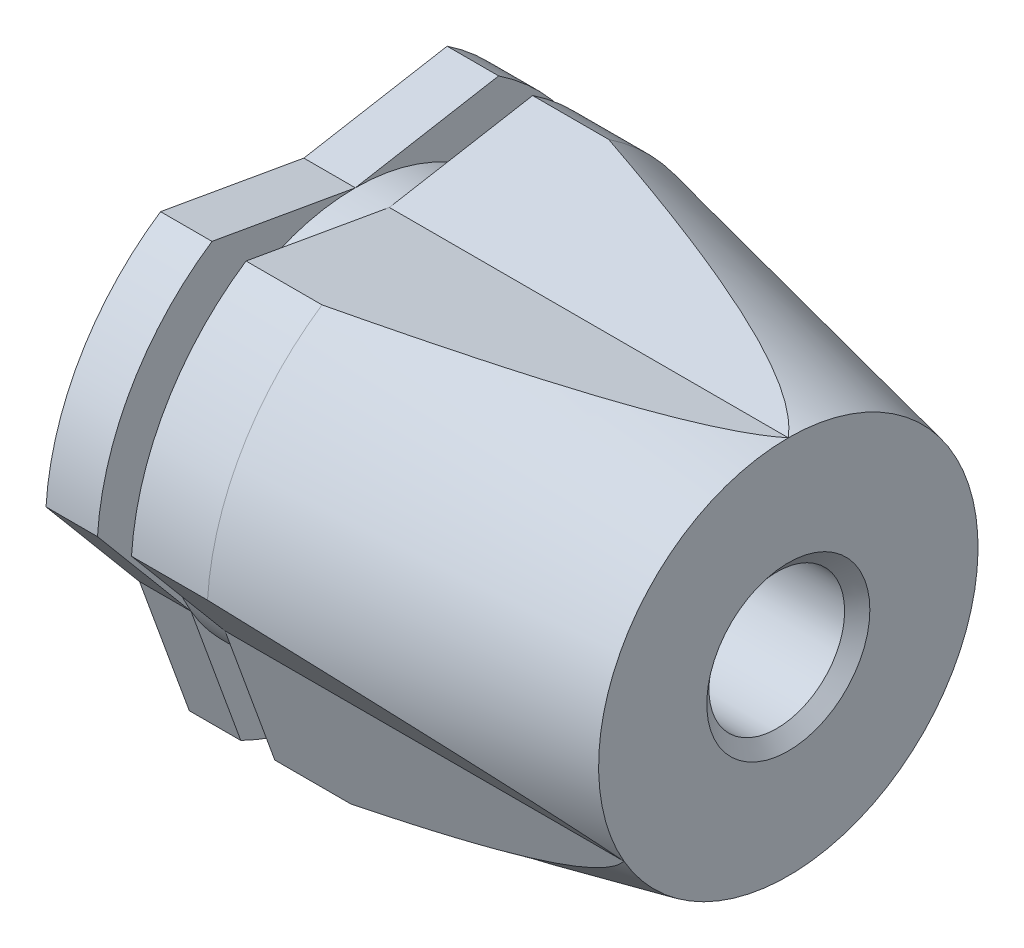
SolidWorks part; units mm, degrees
material "1023 Carbon Steel Sheet (SS)"
ref_plane "Front Plane" through (0, 0, 0) normal (0, 0, 1) x (1, 0, 0)
ref_plane "Top Plane" through (0, 0, 0) normal (0, 1, 0) x (1, 0, 0)
ref_plane "Right Plane" through (0, 0, 0) normal (1, 0, 0) x (0, 0, -1)
sketch "Sketch1" plane through (0, 0, 0) normal (1, 0, 0) x (0, 0, -1)
  circle A0 centre (0, 0) radius 8
  dimension "D1" = 16
extrude "Boss-Extrude1" add sketch "Sketch1" along normal blind 5
sketch "Sketch2" plane through (5, 0, 0) normal (1, 0, 0) x (0, 0, -1)
  circle A0 centre (0, 0) radius 8 construction
  circle A1 centre (0, 0) radius 8
extrude "Boss-Extrude2" add sketch "Sketch2" along normal blind 10 draft 12
sketch "Sketch3" plane through (15, 0, 0) normal (1, 0, 0) x (0, 0, -1)
  line L0 (0, 0) -> (0, 11.4181) construction
  line L1 (0, 5.8744) -> (11.4069, 7.8858)
  line L2 (0, 5.8744) -> (-10.0709, 7.6502)
  circle A0 centre (0, 0) radius 5.8744 construction
  circle A1 centre (0, 0) radius 5.8744
  arc A2 (-10.0709, 7.6502) -> (11.4069, 7.8858) centre (0.6901, 5.7528) cw
  dimension "D1" = 80
  dimension "D2" = 80
  dimension "D3" = 10.0709
  dimension "D4" = 10.927
extrude "Cut-Extrude5" cut sketch "Sketch3" against normal through all
pattern_circular "CirPattern1" count 3 over 360 about axis through (0, 0, 0) along (1, 0, 0) of "Cut-Extrude5"
sketch "Sketch4" plane through (15, 0, 0) normal (1, 0, 0) x (0, 0, -1)
  point P0 (0, 0)
  point P3 (0, 0)
  point P5 (0, 0)
hole_wizard "M5 Tapped Hole1" positions "Sketch4" profile "Sketch5" tap size "M5" standard "ISO" end condition through all
sketch "Sketch5" plane through (15, 0, 0) normal (0, 1, 0) x (0, 0, -1)
  line L0 (0, 0) -> (0, 15)
  line L1 (0, 15) -> (2.1, 15)
  line L2 (2.1, 15) -> (2.1, 0.3566)
  line L3 (2.1, 0.3566) -> (2.525, 0)
  line L5 (2.525, 0) -> (0, 0)
  line L6 (-2.1, 0.3566) -> (-2.525, 0) construction
  line L11 (0, -6.35) -> (0, 107.95) construction
  dimension "Thru Tap Drill Dia." = 4.2
  dimension "Thru Tap Drill Depth" = 15
  dimension "Near C'Sink Dia." = 5.05
  dimension "Near C'Sink Angle" = 100
cosmetic thread "Hole Thread2" parameters "D2"=5
cosmetic thread "Hole Thread3" parameters "D2"=5.85
sketch "Sketch6" plane through (0, 0, 0) normal (0, 0, 1) x (1, 0, 0)
  line L0 (0, 5.8744) -> (15, 5.8744) construction
  line L1 (1.5938, 5.8744) -> (2.6473, 5.8744)
  line L2 (1.5938, 5.8744) -> (1.5938, 8.9058)
  line L3 (1.5938, 8.9058) -> (2.6473, 8.9058)
  line L4 (2.6473, 5.8744) -> (2.6473, 8.9058)
ref_axis "Axis1" through (0, 0, 0) along (1, 0, 0)
revolve "Cut-Revolve2" cut sketch "Sketch6" angle 360 about axis through (0, 0, 0) along (1, 0, 0)
